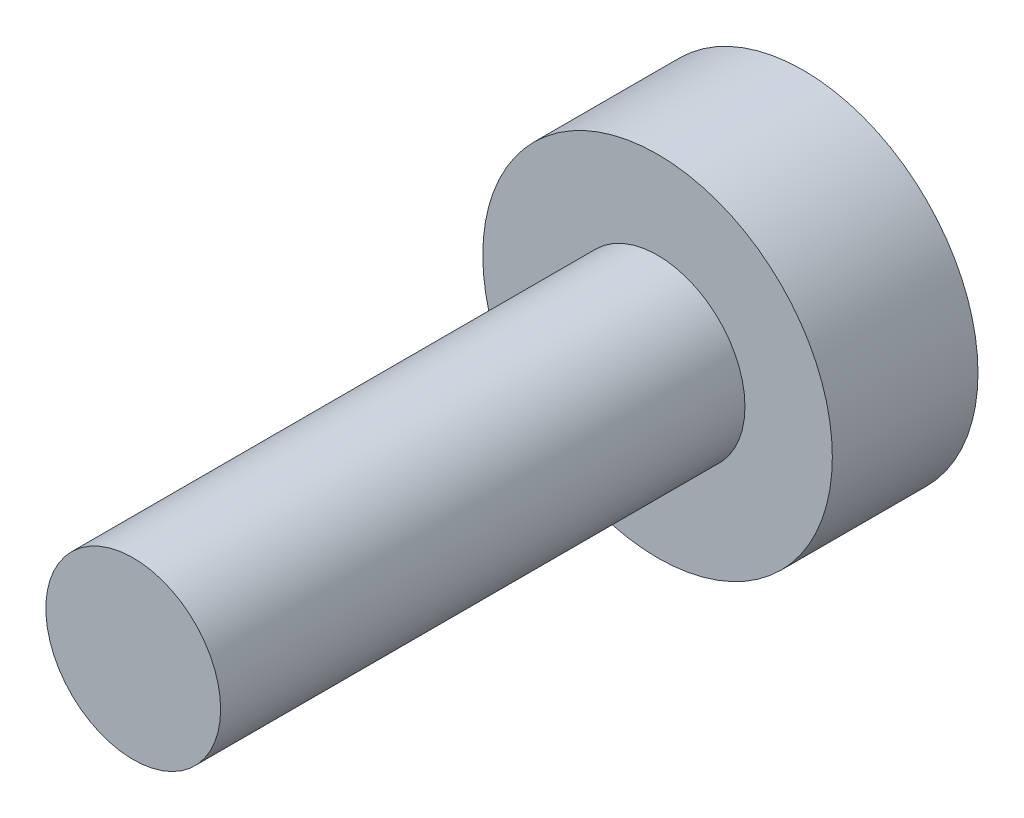
SolidWorks part; units mm, degrees
ref_plane "前视基准面" through (0, 0, 0) normal (0, 0, 1) x (1, 0, 0)
ref_plane "上视基准面" through (0, 0, 0) normal (0, 1, 0) x (1, 0, 0)
ref_plane "右视基准面" through (0, 0, 0) normal (1, 0, 0) x (0, 0, -1)
sketch "草图1" plane through (0, 0, 0) normal (0, 0, 1) x (1, 0, 0)
  circle A0 centre (-5.9441, 3.0062) radius 1.5
  dimension "D1" = 3
extrude "凸台-拉伸1" add sketch "草图1" along normal blind 9
sketch "草图2" plane through (0, 0, 0) normal (0, 0, -1) x (-1, 0, 0)
  circle A4 centre (5.9441, 3.0062) radius 3
  dimension "D1" = 6
extrude "凸台-拉伸2" add sketch "草图2" along normal blind 2.5
sketch "草图4" plane through (0, 0, -2.5) normal (0, 0, -1) x (-1, 0, 0)
  line L0 (2.9441, 3.0062) -> (8.9441, 3.0062) construction
  line L1 (5.9441, 6.0062) -> (5.9441, 0.0062) construction
  line L2 (8.0654, 0.8849) -> (3.8228, 5.1275) construction
  line L3 (3.9441, 3.2562) -> (5.6941, 3.2562)
  line L4 (3.9441, 3.2562) -> (3.9441, 2.7562)
  line L5 (3.9441, 2.7562) -> (5.6941, 2.7562)
  line L6 (7.9441, 3.2562) -> (7.9441, 2.7562)
  line L7 (6.1941, 5.0062) -> (6.1941, 3.2562)
  line L8 (5.6941, 1.0062) -> (6.1941, 1.0062)
  line L9 (5.6941, 5.0062) -> (5.6941, 3.2562)
  line L10 (5.6941, 5.0062) -> (6.1941, 5.0062)
  line L11 (5.6941, 2.7562) -> (5.6941, 1.0062)
  line L12 (6.1941, 2.7562) -> (7.9441, 2.7562)
  line L13 (6.1941, 2.7562) -> (6.1941, 1.0062)
  line L14 (6.1941, 3.2562) -> (7.9441, 3.2562)
  circle A0 centre (5.9441, 3.0062) radius 3 construction
  point P5 (5.9441, 3.0062)
  point P7 (5.9441, 3.0062)
  point P10 (5.9441, 3.0062)
  point P16 (5.9441, 3.0062)
  dimension "D1" = 4
  dimension "D2" = 2
  dimension "D3" = 0.5
  dimension "D4" = 0.25
extrude "切除-拉伸3" cut sketch "草图4" against normal blind 1 contours L3 L9 L10 L7 L14 L6 L12 L13 L8 L11 L5 L4
